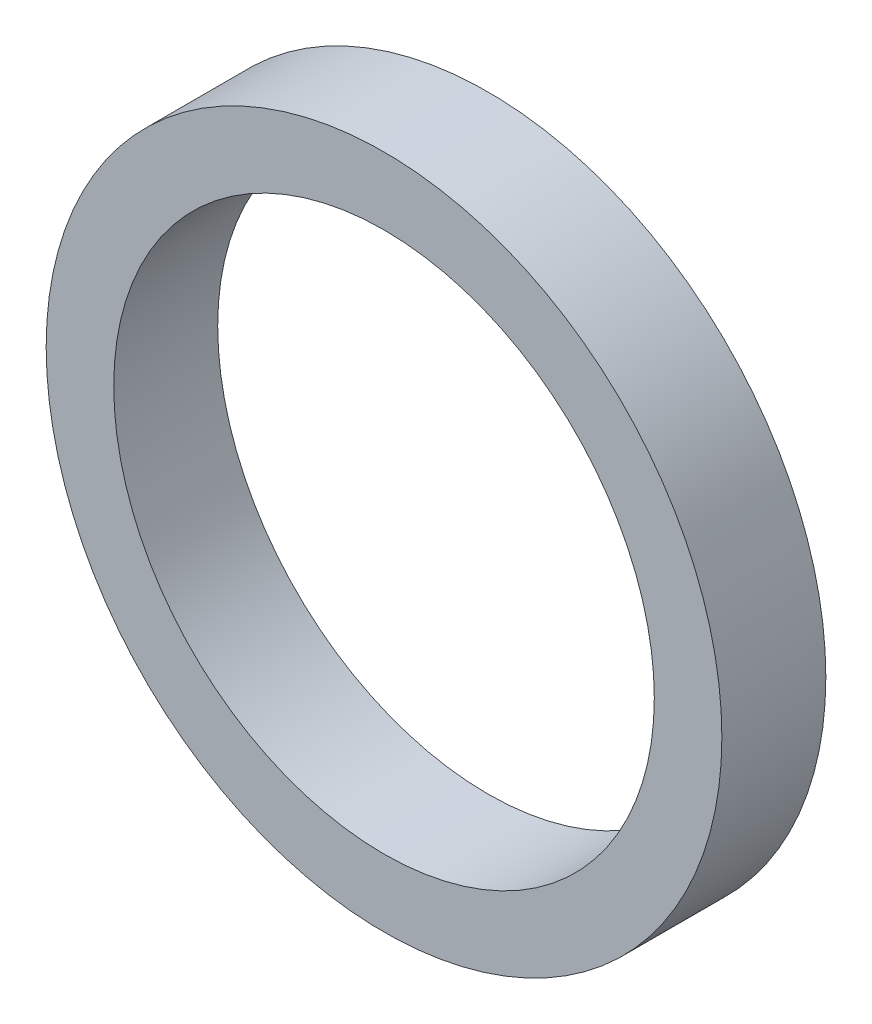
SolidWorks part; units mm, degrees
ref_plane "Front Plane" through (0, 0, 0) normal (0, 0, 1) x (1, 0, 0)
ref_plane "Top Plane" through (0, 0, 0) normal (0, 1, 0) x (1, 0, 0)
ref_plane "Right Plane" through (0, 0, 0) normal (1, 0, 0) x (0, 0, -1)
sketch "Sketch1" plane through (0, 0, 3) normal (0, 0, 1) x (1, 0, 0)
  circle A0 centre (33, 0) radius 2.6
  circle A1 centre (33, 0) radius 3.25
  dimension "D1" = 5.2
  dimension "D2" = 6.5
extrude "Boss-Extrude1" add sketch "Sketch1" along normal blind 1
